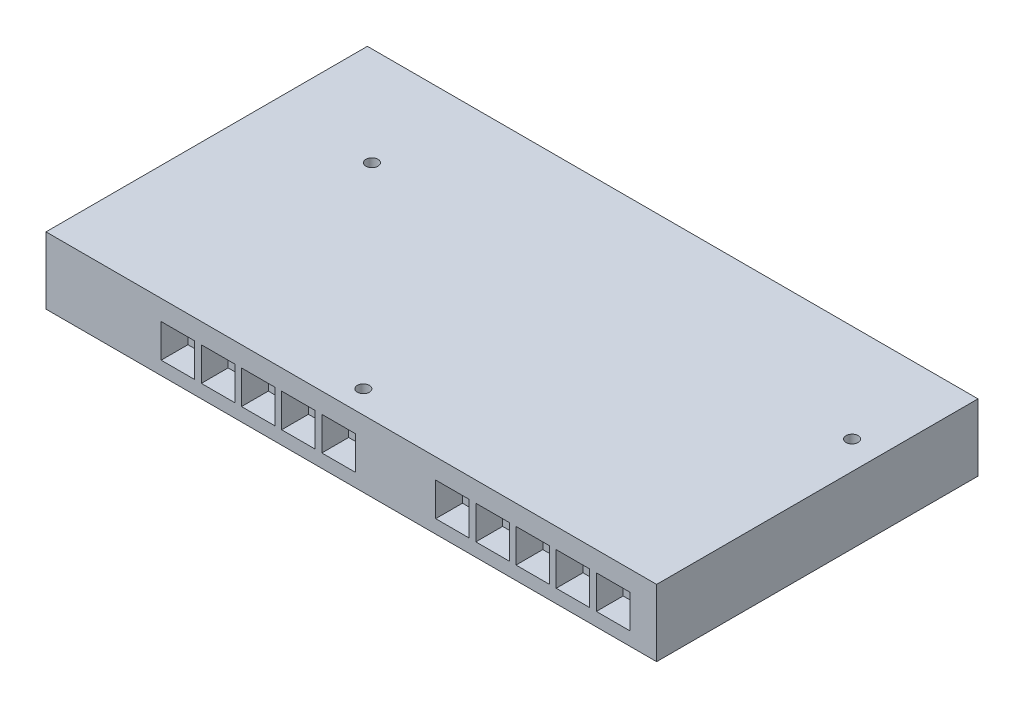
SolidWorks part; units mm, degrees
ref_plane "Front" through (0, 0, 0) normal (0, 0, 1) x (1, 0, 0)
ref_plane "Top" through (0, 0, 0) normal (0, 1, 0) x (1, 0, 0)
ref_plane "Right" through (0, 0, 0) normal (1, 0, 0) x (0, 0, -1)
sketch "Sketch1" plane through (0, 0, 0) normal (0, 0, 1) x (1, 0, 0)
  line L1 (-114, 12.5) -> (114, 12.5)
  line L2 (-114, 12.5) -> (-114, -12.5)
  line L3 (-114, -12.5) -> (114, -12.5)
  line L4 (114, 12.5) -> (114, -12.5)
  line L5 (-114, 12.5) -> (114, -12.5) construction
  line L6 (-114, -12.5) -> (114, 12.5) construction
  point P0 (0, 0)
  dimension "D1" = 228
  dimension "D2" = 25
extrude "Boss-Extrude1" add sketch "Sketch1" along normal mid plane 120
sketch "Sketch3" plane through (0, 0, 60) normal (0, 0, 1) x (1, 0, 0)
  line L0 (76.5, 5) -> (89, 5)
  line L1 (91.5, 5) -> (104, 5)
  line L2 (91.5, 5) -> (91.5, -7.5)
  line L3 (91.5, -7.5) -> (104, -7.5)
  line L4 (104, 5) -> (104, -7.5)
  line L5 (91.5, 5) -> (104, -7.5) construction
  line L6 (91.5, -7.5) -> (104, 5) construction
  line L7 (76.5, 5) -> (76.5, -7.5)
  line L8 (76.5, -7.5) -> (89, -7.5)
  line L9 (89, 5) -> (89, -7.5)
  line L10 (76.5, 5) -> (89, -7.5) construction
  line L11 (76.5, -7.5) -> (89, 5) construction
  line L12 (61.5, 5) -> (74, 5)
  line L13 (61.5, 5) -> (61.5, -7.5)
  line L14 (61.5, -7.5) -> (74, -7.5)
  line L15 (74, 5) -> (74, -7.5)
  line L16 (61.5, 5) -> (74, -7.5) construction
  line L17 (61.5, -7.5) -> (74, 5) construction
  line L18 (46.5, 5) -> (59, 5)
  line L19 (46.5, 5) -> (46.5, -7.5)
  line L20 (46.5, -7.5) -> (59, -7.5)
  line L21 (59, 5) -> (59, -7.5)
  line L22 (46.5, 5) -> (59, -7.5) construction
  line L23 (46.5, -7.5) -> (59, 5) construction
  line L24 (31.5, 5) -> (44, 5)
  line L25 (31.5, 5) -> (31.5, -7.5)
  line L26 (31.5, -7.5) -> (44, -7.5)
  line L27 (44, 5) -> (44, -7.5)
  line L28 (31.5, 5) -> (44, -7.5) construction
  line L29 (31.5, -7.5) -> (44, 5) construction
  line L30 (114, -12.5) -> (114, 12.5) construction
  line L31 (-114, -12.5) -> (114, -12.5) construction
  point P0 (97.75, -1.25)
  point P5 (82.75, -1.25)
  point P12 (67.75, -1.25)
  point P17 (52.75, -1.25)
  point P22 (37.75, -1.25)
  dimension "D1" = 10
  dimension "D2" = 5
  dimension "D3" = 12.5
  dimension "D5" = 15
  dimension "D4" = 5
extrude "Cut-Extrude2" cut sketch "Sketch3" against normal blind 10
pattern_linear "LPattern1" count 2 spacing 102.5 along (-1, 0, 0) of "Cut-Extrude2"
sketch "Sketch6" plane through (0, 0, -60) normal (0, 0, -1) x (-1, 0, 0)
  line L0 (103, 0) -> (-103, 0) construction
  line L1 (29, 0) -> (-29, 0) construction
  line L2 (114, 12.5) -> (114, -12.5) construction
  circle A0 centre (-103, 0) radius 7
  circle A1 centre (-29, 0) radius 7
  circle A2 centre (29, 0) radius 7
  circle A3 centre (103, 0) radius 7
  point P4 (0, 0)
  point P8 (0, 0)
  dimension "D3" = 14
  dimension "D1" = 11
  dimension "D2" = 85
sketch "Sketch7" plane through (0, -12.5, 0) normal (0, -1, 0) x (1, 0, 0)
  line L0 (0, -60) -> (0, 7.5) construction
  line L1 (84, 40) -> (-84, 40) construction
  line L2 (84, 40) -> (84, -25) construction
  line L3 (84, -25) -> (-84, -25) construction
  line L4 (-84, 40) -> (-84, -25) construction
  line L5 (84, 40) -> (-84, -25) construction
  line L6 (84, -25) -> (-84, 40) construction
  line L7 (-114, -60) -> (114, -60) construction
  line L8 (-114, 60) -> (-114, -60) construction
  circle A0 centre (-84, -25) radius 7.5
  circle A1 centre (-84, 40) radius 7.5
  circle A2 centre (84, 40) radius 7.5
  circle A3 centre (84, -25) radius 7.5
  point P2 (0, 7.5)
  dimension "D4" = 15
  dimension "D1" = 35
  dimension "D2" = 100
  dimension "D3" = 30
extrude "Boss-Extrude4" add sketch "Sketch7" along normal blind 3 draft 20
hole_wizard "M3x0.5 Tapped Hole1" positions "Sketch10" profile "Sketch11" tap size "M3x0.5" standard "ANSI Metric"
sketch "Sketch10" plane through (0, -12.5, 0) normal (0, -1, 0) x (-1, 0, 0)
  line L0 (-105.75, -25) -> (105.75, -25) construction
  line L2 (0, -60) -> (0, -25) construction
  line L3 (114, -60) -> (-114, -60) construction
  point P2 (105.75, -25)
  point P38 (-105.75, -25)
  dimension "D1" = 211.5
  dimension "D2" = 35
sketch "Sketch11" plane through (-105.75, -12.5, 25) normal (1, 0, 0) x (0, 0, -1)
  line L0 (0, 0) -> (0, 5.7511)
  line L1 (0, 5.7511) -> (1.25, 5)
  line L2 (1.25, 5) -> (1.25, 0)
  line L5 (1.25, 0) -> (0, 0)
  line L10 (0, 5.7511) -> (-1.25, 5) construction
  line L11 (0, -6.35) -> (0, 107.95) construction
  dimension "Tap Drill Dia." = 2.5
  dimension "Tap Drill Depth" = 5
  dimension "Drill Angle" = 118
cosmetic thread "Hole Thread1" parameters "D1"=5, "D2"=3
cosmetic thread "Hole Thread2" parameters "D1"=5, "D2"=3
sketch "Sketch12" plane through (0, -12.5, 0) normal (0, -1, 0) x (1, 0, 0)
  line L0 (-114, -60) -> (114, -60) construction
  line L1 (-94, -60) -> (-59, -60)
  line L2 (-94, -60) -> (-94, -35)
  line L3 (-94, -35) -> (-59, -35)
  line L4 (-59, -60) -> (-59, -35)
  line L5 (-114, 60) -> (-114, -60) construction
  dimension "D1" = 20
  dimension "D2" = 25
  dimension "D3" = 35
extrude "Cut-Extrude3" cut sketch "Sketch12" against normal offset from surface (15 mm away) 10 up to face at (0, 12.5, 0)
extrude "Cut-Extrude4" cut sketch "Sketch6" against normal blind 10
hole_wizard "Ø4.5 (4.5) Drill Bit for PEM Nuts" positions "Sketch15" profile "Sketch14" hole size "Ø4.5" standard "ANSI Metric"
sketch "Sketch15" plane through (0, 12.5, 0) normal (0, 1, 0) x (1, 0, 0)
  line L0 (114, -60) -> (-114, -60) construction
  line L3 (114, -60) -> (114, 60) construction
  line L4 (-114, -60) -> (-114, 60) construction
  line L5 (114, 60) -> (-114, 60) construction
  point P0 (-4, -51.5)
  point P2 (-75.5, 23.2)
  point P14 (103.5, 23.5)
  dimension "D1" = 36.8
  dimension "D2" = 110
  dimension "D3" = 38.5
  dimension "D4" = 36.5
  dimension "D5" = 10.5
  dimension "D6" = 8.5
sketch "Sketch14" plane through (-4, 12.5, 51.5) normal (1, 0, 0) x (0, 0, 1)
  line L0 (0, 0) -> (0, 6.3519)
  line L1 (0, 6.3519) -> (2.25, 5)
  line L2 (2.25, 5) -> (2.25, 0)
  line L5 (2.25, 0) -> (0, 0)
  line L10 (0, 6.3519) -> (-2.25, 5) construction
  line L11 (0, -6.35) -> (0, 107.95) construction
  dimension "Hole Dia." = 4.5
  dimension "Hole Depth" = 5
  dimension "Drill Angle" = 118
